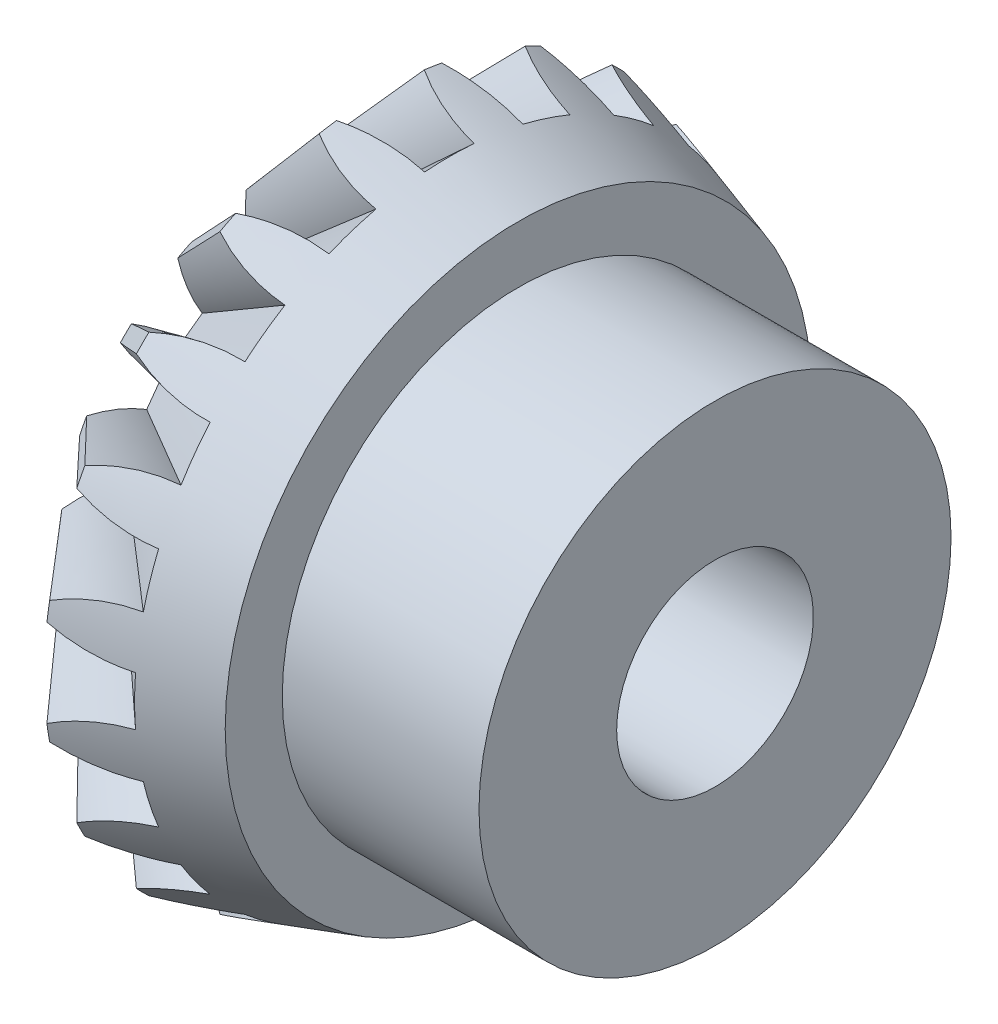
SolidWorks part; units mm, degrees
ref_plane "Front" through (0, 0, 0) normal (0, 0, 1) x (1, 0, 0)
ref_plane "Top" through (0, 0, 0) normal (0, 1, 0) x (1, 0, 0)
ref_plane "Right" through (0, 0, 0) normal (1, 0, 0) x (0, 0, -1)
sketch "Sketch1" plane through (0, 0, 0) normal (0, 0, 1) x (1, 0, 0)
  line L0 (0, 0) -> (10.8, 0) construction
  line L1 (0, 2.5) -> (10.8, 2.5)
  line L2 (10.8, 2.5) -> (10.8, 6)
  line L3 (10.8, 6) -> (5.8, 6)
  line L4 (5.8, 6) -> (5.8, 7.45)
  line L5 (5.8, 7.45) -> (2.2956, 8.55)
  line L6 (2.2956, 8.55) -> (0, 5.908)
  line L7 (0, 5.908) -> (0, 2.5)
  line L8 (4.0478, 8) -> (0, 3.3414) construction
  dimension "D1" = 49.013
  dimension "Overall Length" = 10.8
  dimension "OD" = 17.1
  dimension "For Shaft" = 5
  dimension "Face Width" = 3.5
  dimension "Hub Dia" = 12
  dimension "Hub Width" = 5
  dimension "PD" = 16
revolve "Revolve1" add sketch "Sketch1" angle 360 about L0
sketch "Sketch2" plane through (0, 0, 0) normal (-1, 0, 0) x (0, 0, 1)
  circle A0 centre (0, 0) radius 8
  dimension "Pitch Dia" = 16
sketch "Sketch3" plane through (0, 0, 0) normal (-1, 0, 0) x (0, 0, 1)
  line L0 (-10, 0) -> (10, 0) construction
  point P2 (0, 0)
  dimension "teeth" = 20
sketch "Sketch5" plane through (0, 0, 0) normal (-1, 0, 0) x (0, 0, 1)
  line L0 (0, 0) -> (0, 8.55) construction
  line L1 (0, 0) -> (0.6708, 8.5236) construction
  line L2 (0, 0) -> (-0.6708, 8.5236) construction
  line L4 (-10, 0) -> (10, 0) construction
  line L5 (-0.3354, 4.2618) -> (0.3354, 4.2618)
  line L6 (0, 0) -> (-2.6421, 8.1315) construction
  line L7 (0, 0) -> (2.6421, 8.1315) construction
  circle A0 centre (0, 0) radius 8.55 construction
  arc A1 (-0.3354, 4.2618) -> (-2.6421, 8.1315) centre (-5.4039, 3.8629) ccw
  arc A2 (0.3354, 4.2618) -> (2.6421, 8.1315) centre (5.4039, 3.8629) cw
  arc A3 (-2.6421, 8.1315) -> (2.6421, 8.1315) centre (0, 0) cw
  point P10 (0, 0)
  dimension "D1" = 9
  dimension "D2" = 36
ref_plane "Plane1" through (4.0478, 0, 0) normal (1, 0, 0) x (0, 0, -1)
sketch "Sketch6" plane through (4.0478, 0, 0) normal (1, 0, 0) x (0, 0, -1)
  line L0 (0, 0) -> (0, 12.825) construction
  line L1 (0, 0) -> (0.6708, 8.5236) construction
  line L2 (0, 0) -> (-0.6708, 8.5236) construction
  line L3 (0, 0) -> (4.1671, 12.825) construction
  line L4 (0, 0) -> (-4.1671, 12.825) construction
  line L5 (4.1671, 12.825) -> (-4.1671, 12.825) construction
  line L6 (0, 8.55) -> (0, 0) construction
  line L7 (-4.1671, 12.825) -> (4.1671, 12.825)
  circle A0 centre (0, 0) radius 8.55 construction
  arc A1 (-0.6277, 7.9753) -> (-4.1671, 12.825) centre (-6.3353, 7.5261) ccw
  arc A2 (0.6277, 7.9753) -> (4.1671, 12.825) centre (6.3353, 7.5261) cw
  circle A3 centre (0, 0) radius 8 construction
  arc A4 (0.6277, 7.9753) -> (-0.6277, 7.9753) centre (0, 0) ccw
  dimension "D1" = 9
  dimension "D2" = 36
  dimension "D3" = 12.825
  dimension "D4" = 8.55
loft "Cut-Loft1" cut profiles "Sketch6", "Sketch5"
pattern_circular "CirPattern1" count 20 over 360 about axis through (0, 0, 0) along (-1, 0, 0) of "Cut-Loft1"
sketch "Sketch7" plane through (0, 0, 0) normal (-1, 0, 0) x (0, 0, 1)
  circle A0 centre (0, 0) radius 8
sketch "Sketch8" plane through (0, 0, 0) normal (0, 1, 0) x (1, 0, 0)
  line L0 (-5.2, 16) -> (-5.2, 5.2) construction
  line L2 (10.8, -6) -> (10.8, 6) construction
  line B0 (-11.0628, 5.2) -> (-13.677, 7.4956) construction
  line B1 (-13.677, 7.4956) -> (-12.65, 11) construction
  line B2 (-12.65, 11) -> (-11.2, 11) construction
  line B3 (-11.2, 11) -> (-11.2, 16) construction
  line B4 (-11.2, 16) -> (0.8, 16) construction
  line B5 (0.8, 16) -> (0.8, 11) construction
  line B6 (0.8, 11) -> (2.25, 11) construction
  line B7 (2.25, 11) -> (3.277, 7.4956) construction
  line B8 (3.277, 7.4956) -> (0.6628, 5.2) construction
  line B9 (0.6628, 5.2) -> (-11.0628, 5.2) construction
  dimension "D1" = 16
  dimension "D2" = 16
sketch_block_instance "Block2-1"
sketch_block "Block2"
equation "\"D1@Sketch5\"=(360deg/20)/2"
equation "\"D2@Sketch5\"=(360deg/20)/.5"
equation "\"D1@Sketch6\"=(360deg/\"teeth@Sketch5\")/2"
equation "\"D2@Sketch6\"=(360deg/\"teeth@Sketch5\")/.5"
equation "\"D3@Sketch6\"=\"D4@Sketch6\"*1.5"
